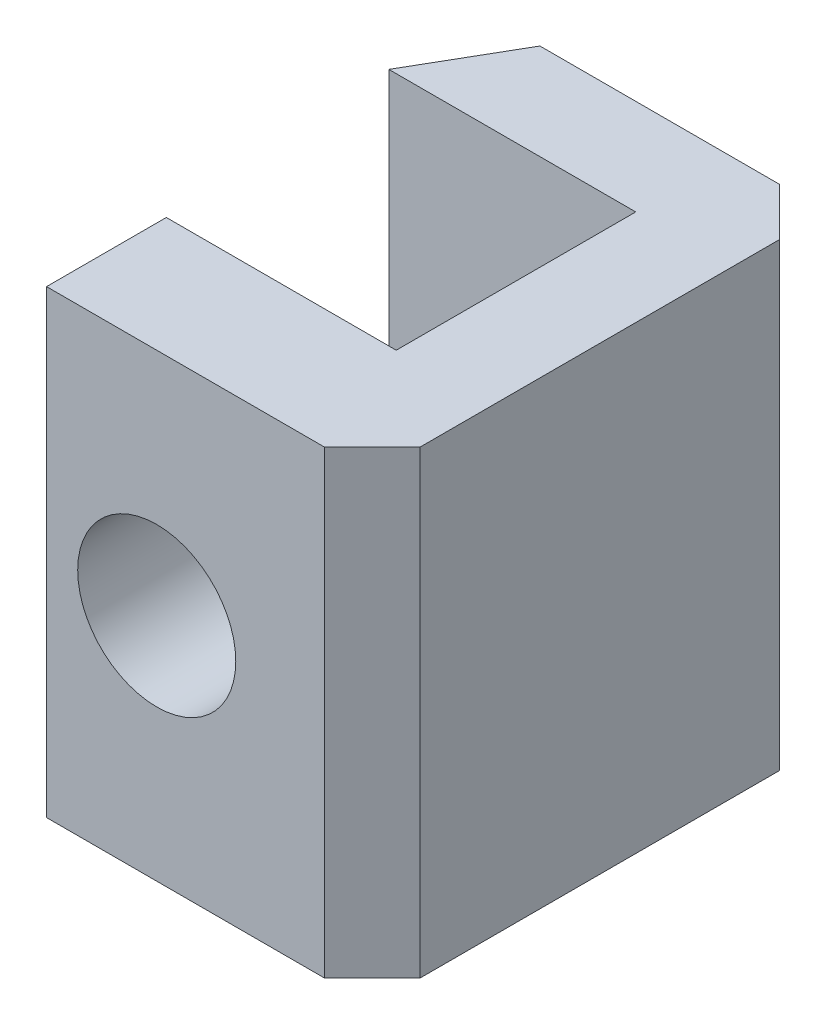
SolidWorks part; units mm, degrees
ref_plane "前视基准面" through (0, 0, 0) normal (0, 0, 1) x (1, 0, 0)
ref_plane "上视基准面" through (0, 0, 0) normal (0, 1, 0) x (1, 0, 0)
ref_plane "右视基准面" through (0, 0, 0) normal (1, 0, 0) x (0, 0, -1)
other "Configuration Table"
sketch "Sketch2" plane through (0, -17.9888, 0) normal (0, -1, 0) x (1, 0, 0)
  line L0 (26.1815, 0) -> (31.1815, 0) construction
  line L1 (21.1815, -5) -> (31.1815, -5) construction
  line L2 (31.1815, -2.5) -> (31.1815, -5) construction
  line L3 (31.1815, -2.5) -> (31.1815, 2.5) construction
  line L4 (26.0268, -5) -> (31.1815, -5)
  line L5 (31.1815, -2.5) -> (31.1815, -5)
  line L6 (31.1815, -2.5) -> (31.1815, 0)
  line L7 (26.3815, 0) -> (31.1815, 0)
  line L9 (26.3815, 2.5) -> (33.1815, 2.5)
  line L10 (26.3815, 0) -> (26.3815, 2.5)
  line L11 (26.3815, 0) -> (26.3815, 2.5)
  line L12 (33.1815, 2.5) -> (33.1815, -7)
  line L13 (33.1815, -7) -> (27.1815, -7)
  line L14 (27.1815, -7) -> (26.0268, -5)
  dimension "D2" = 60
  dimension "D3" = 2
  dimension "D4" = 6
  dimension "D5" = 2
  dimension "D1" = 0.2
extrude "Boss-Extrude1" add sketch "Sketch2" along normal offset from surface (9.6 mm away) 0.2 from offset 0.2
sketch "Sketch3" plane through (0, 0, 2.5) normal (0, 0, 1) x (1, 0, 0)
  line L0 (31.1815, -17.9888) -> (31.1815, -10.1297) construction
  line L1 (31.1815, -17.9888) -> (26.1815, -17.9888) construction
  circle A0 centre (28.6815, -22.9888) radius 1.65
  dimension "D1" = 3.3
  dimension "D2" = 2.5
  dimension "D3" = 5
extrude "Cut-Extrude1" cut sketch "Sketch3" against normal blind 5
chamfer "Chamfer1" distance 1 angle 45 2 edges at (33.1815, -22.9888, -7) (33.1815, -22.9888, 2.5)
